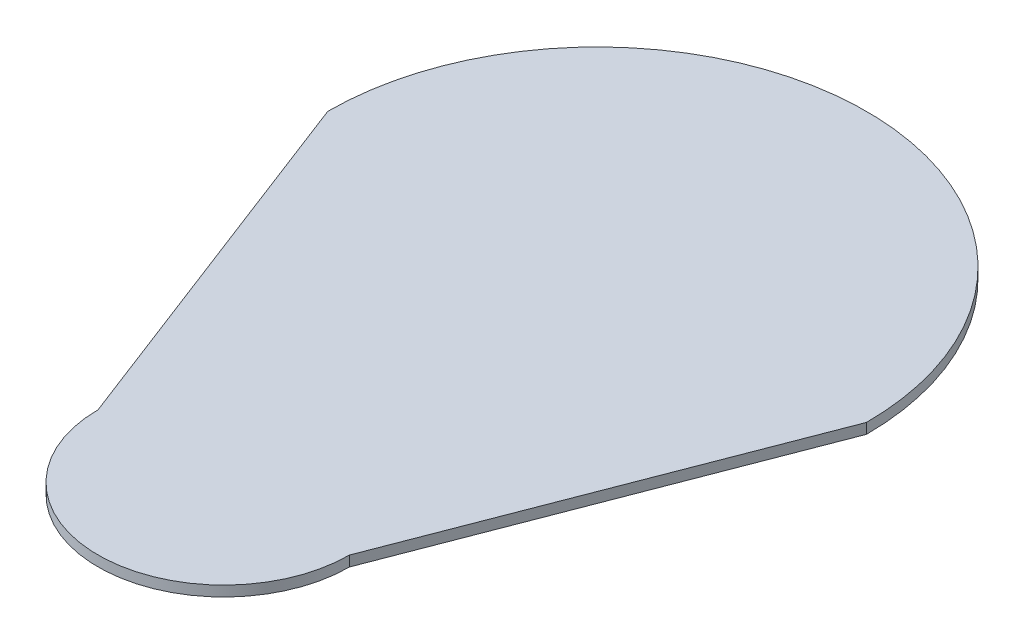
SolidWorks part; units mm, degrees
ref_plane "Alzado" through (0, 0, 0) normal (0, 0, 1) x (1, 0, 0)
ref_plane "Planta" through (0, 0, 0) normal (0, 1, 0) x (1, 0, 0)
ref_plane "Vista lateral" through (0, 0, 0) normal (1, 0, 0) x (0, 0, -1)
sketch "Croquis1" plane through (0, 0, 0) normal (0, 1, 0) x (1, 0, 0)
  line L0 (60.6902, -180.1773) -> (130, 0)
  line L1 (-60.6902, -180.1773) -> (-130, 0)
  circle A0 centre (0, 0) radius 130
  circle A1 centre (0, -180.1773) radius 60.6902
  dimension "D1" = 260
extrude "Saliente-Extruir1" add sketch "Croquis1" along normal blind 5 contours A1 A0 L0 L1 | A1 A0 | A1 L0 A0 | A1 A0 L1
